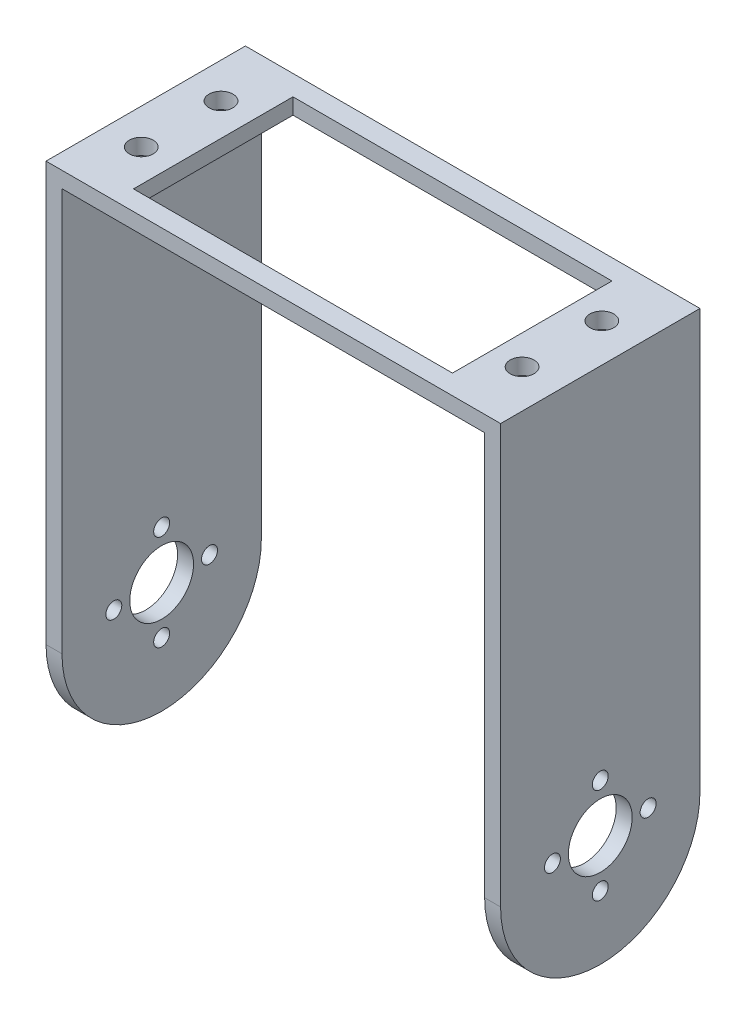
SolidWorks part; units mm, degrees
material "1060 Alloy"
ref_plane "Front Plane" through (0, 0, 0) normal (0, 0, 1) x (1, 0, 0)
ref_plane "Top Plane" through (0, 0, 0) normal (0, 1, 0) x (1, 0, 0)
ref_plane "Right Plane" through (0, 0, 0) normal (1, 0, 0) x (0, 0, -1)
sketch "Sketch3" plane through (0, 0, 0) normal (0, 0, 1) x (1, 0, 0)
  line L0 (-79.9255, 45.3865) -> (-27.043, 45.3865)
  line L1 (-81.9255, 45.3865) -> (-79.9255, 45.3865)
  line L2 (-81.9255, 45.3865) -> (-81.9255, -19.6135)
  line L3 (-81.9255, -19.6135) -> (-79.9255, -19.6135)
  line L4 (-79.9255, 43.39) -> (-79.9255, -19.6135)
  line L5 (-81.9255, 45.3865) -> (-79.9255, -19.6135) construction
  line L6 (-81.9255, -19.6135) -> (-79.9255, 45.3865) construction
  line L7 (-79.9255, 43.39) -> (-26.9255, 43.39)
  line L8 (-26.9255, 43.39) -> (-26.9255, -19.6135)
  line L9 (-27.043, 45.3865) -> (-24.9255, 45.3865)
  line L10 (-26.9255, -19.6135) -> (-24.9255, -19.6135)
  line L11 (-24.9255, 45.3865) -> (-24.9255, -19.6135)
  point P0 (-80.9255, 12.8865)
  dimension "D1" = 65
  dimension "D2" = 2
  dimension "D3" = 2
  dimension "D4" = 57
  dimension "D5" = 2
extrude "Boss-Extrude2" add sketch "Sketch3" along normal blind 25
sketch "Sketch4" plane through (0, 45.3865, 0) normal (0, 1, 0) x (1, 0, 0)
  line L0 (-81.9255, -25) -> (-81.9255, 0) construction
  line L3 (-24.9255, -25) -> (-81.9255, -25) construction
  circle A0 centre (-54.9255, -12.5) radius 4
  dimension "D1" = 27
  dimension "D2" = 12.5
extrude "Cut-Extrude1" cut sketch "Sketch4" against normal through all
sketch "Sketch6" plane through (-81.9255, 0, 0) normal (-1, 0, 0) x (0, 0, 1)
  line L1 (25, 45.3865) -> (0, 45.3865) construction
  line L2 (0, 45.3865) -> (0, -19.6135) construction
  circle A0 centre (12.5, -5.6135) radius 4
  dimension "D1" = 51
  dimension "D2" = 12.5
extrude "Cut-Extrude2" cut sketch "Sketch6" against normal through all
sketch "Sketch8" plane through (-81.9255, 0, 0) normal (-1, 0, 0) x (0, 0, 1)
  line L0 (25, 45.3865) -> (25, -19.6135) construction
  line L1 (25, -19.6135) -> (0, -19.6135) construction
  line L2 (0, 45.3865) -> (0, -19.6135) construction
  line L3 (25, -19.6135) -> (0, -19.6135)
  line L4 (0, 45.3865) -> (0, -19.6135)
  line L5 (25, 45.3865) -> (25, -19.6135)
  circle A0 centre (12.5, -7.1135) radius 12.5
  line M4 (0, -19.6135) -> (25, -19.6135)
  line M5 (25, -19.6135) -> (25, 45.3865)
extrude "Cut-Extrude3" cut sketch "Sketch8" against normal through all contours A0 L4 M4 | A0 L3 M5
sketch "Sketch9" plane through (-24.9255, 0, 0) normal (1, 0, 0) x (0, 0, -1)
  circle A0 centre (-6.5, -5.6135) radius 1
  circle A2 centre (-12.5, -11.6135) radius 1
  circle A3 centre (-18.5, -5.6135) radius 1
  circle A5 centre (-12.5, -5.6135) radius 6 construction
  circle A6 centre (-12.5, 0.3865) radius 1
  point P12 (-12.5, -5.6135)
  point P13 (-12.5, -5.6135)
  dimension "D1" = 4
  dimension "D3" = 12
  dimension "D4" = 2
extrude "Cut-Extrude4" cut sketch "Sketch9" against normal through all
sketch "Sketch10" plane through (0, 45.3865, 0) normal (0, 1, 0) x (1, 0, 0)
  circle A0 centre (-60.9255, -12.155) radius 1
  circle A2 centre (-54.5805, -6.5) radius 1
  circle A3 centre (-48.9255, -12.845) radius 1
  circle A4 centre (-55.2705, -18.5) radius 1
  point P13 (-54.9255, -12.5)
  dimension "D2" = 4
extrude "Cut-Extrude5" cut sketch "Sketch10" against normal through all
sketch "Sketch11" plane through (0, 45.3865, 0) normal (0, 1, 0) x (1, 0, 0)
  line L1 (-81.9255, -25) -> (-81.9255, 0) construction
  line L2 (-73.4255, -2.5357) -> (-33.4255, -2.5357)
  line L3 (-73.4255, -2.5357) -> (-73.4255, -22.5357)
  line L4 (-73.4255, -22.5357) -> (-33.4255, -22.5357)
  line L5 (-33.4255, -2.5357) -> (-33.4255, -22.5357)
  line L8 (-81.9255, -12.5) -> (-24.9255, -12.5) construction
  line L9 (-24.9255, -25) -> (-24.9255, 0) construction
  circle A1 centre (-77.4868, -7.5) radius 1.5
  circle A2 centre (-77.4868, -17.5) radius 1.5
  circle A3 centre (-29.7326, -17.5) radius 1.5
  circle A4 centre (-29.7326, -7.5) radius 1.5
  dimension "D4" = 3
  dimension "D1" = 20
  dimension "D2" = 40
  dimension "D3" = 8.5
  dimension "D5" = 10
  dimension "D6" = 10
extrude "Cut-Extrude6" cut sketch "Sketch11" against normal blind 10
